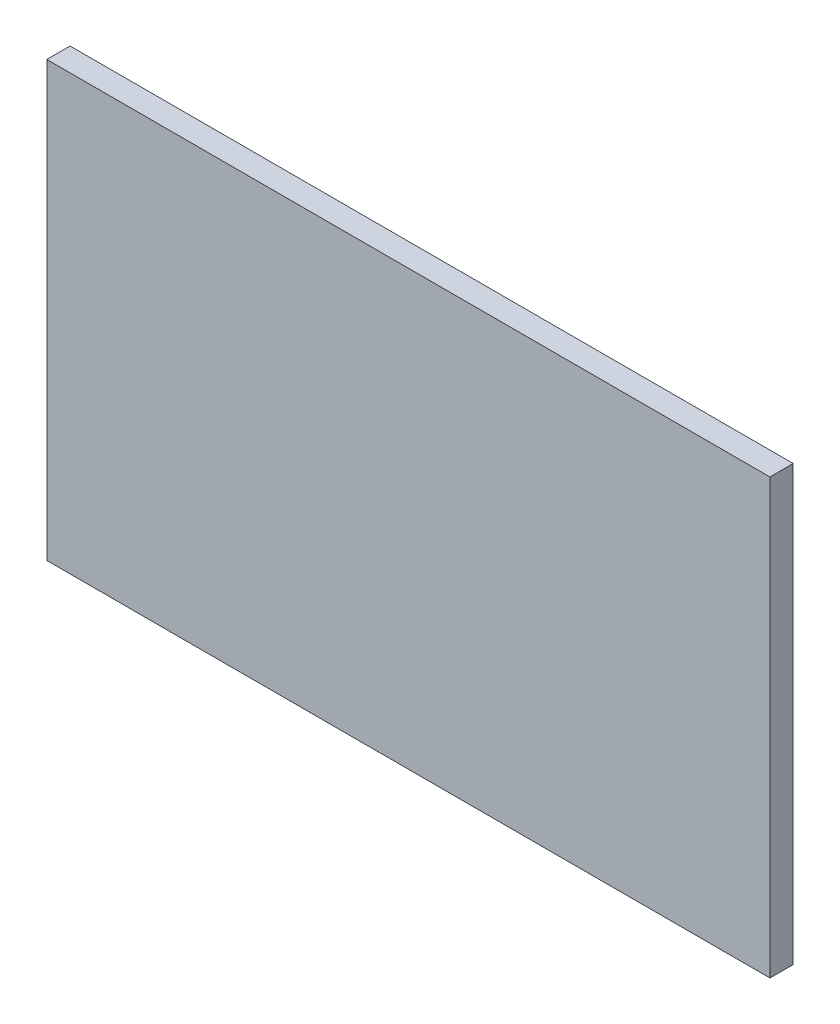
SolidWorks part; units mm, degrees
ref_plane "Front Plane" through (0, 0, 0) normal (0, 0, 1) x (1, 0, 0)
ref_plane "Top Plane" through (0, 0, 0) normal (0, 1, 0) x (1, 0, 0)
ref_plane "Right Plane" through (0, 0, 0) normal (1, 0, 0) x (0, 0, -1)
sketch "Croquis1" plane through (0, 0, 0) normal (0, 0, 1) x (1, 0, 0)
  line L1 (0, 0) -> (50, 0)
  line L2 (0, 0) -> (0, -30)
  line L3 (0, -30) -> (50, -30)
  line L4 (50, 0) -> (50, -30)
extrude "Saliente-Extruir1" add sketch "Croquis1" along normal blind 1.61
